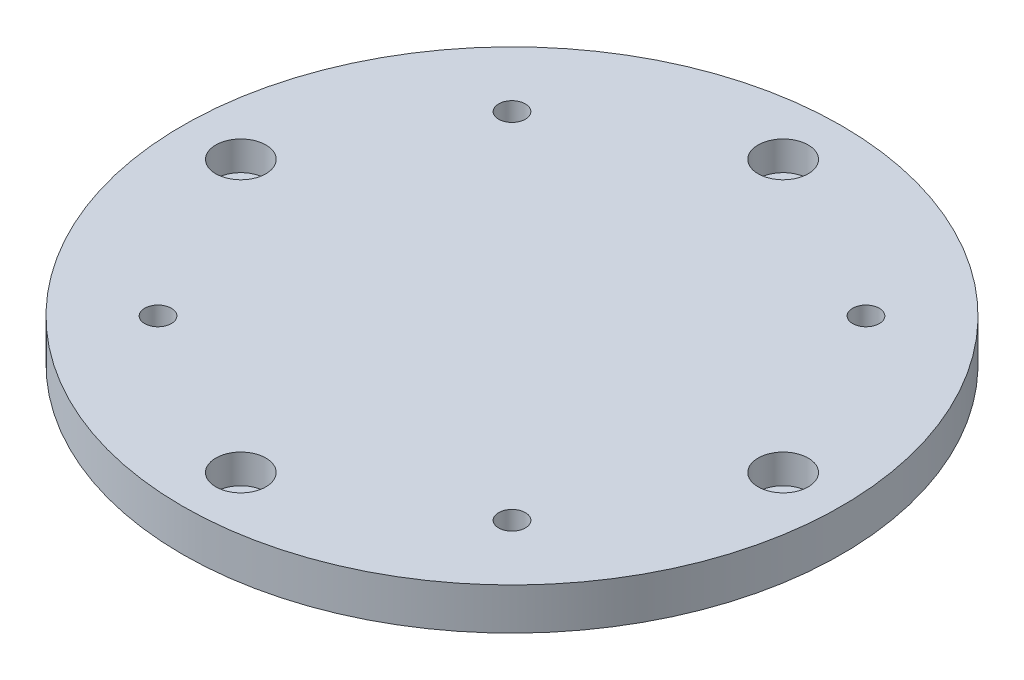
SolidWorks part; units mm, degrees
ref_plane "前视基准面" through (0, 0, 0) normal (0, 0, 1) x (1, 0, 0)
ref_plane "上视基准面" through (0, 0, 0) normal (0, 1, 0) x (1, 0, 0)
ref_plane "右视基准面" through (0, 0, 0) normal (1, 0, 0) x (0, 0, -1)
other "Configuration Table"
sketch "草图1" plane through (0, 0, 0) normal (0, 1, 0) x (1, 0, 0)
  circle A0 centre (0, 0) radius 39.5
  dimension "D1" = 79
extrude "凸台-拉伸1" add sketch "草图1" along normal blind 5
sketch "草图2" plane through (0, 5, 0) normal (0, 1, 0) x (1, 0, 0)
  line L0 (0, 37.2388) -> (0, -16.3257) construction
  line L1 (-34.8929, 0) -> (38.863, 0) construction
  circle A0 centre (0, 0) radius 32.5 construction
  circle A1 centre (0, 32.5) radius 1.5
  circle A2 centre (32.5, 0) radius 1.5
  circle A3 centre (0, -32.5) radius 1.5
  circle A4 centre (-32.5, 0) radius 1.5
  dimension "D1" = 65
  dimension "D2" = 3
  dimension "D3" = 3
  dimension "D4" = 3
  dimension "D5" = 3
extrude "切除-拉伸1" cut sketch "草图2" against normal through all both
sketch "草图3" plane through (0, 5, 0) normal (0, 1, 0) x (1, 0, 0)
  circle A0 centre (-32.5, 0) radius 3
  circle A1 centre (0, -32.5) radius 3
  circle A2 centre (32.5, 0) radius 3
  circle A3 centre (0, 32.5) radius 3
  dimension "D1" = 6
extrude "切除-拉伸2" cut sketch "草图3" against normal blind 3.5
sketch "草图5" plane through (0, 0, 0) normal (0, -1, 0) x (1, 0, 0)
  line L0 (0, 0) -> (21.2132, 21.2132) construction
  line L1 (0, 0) -> (30, 0) construction
  circle A0 centre (0, 0) radius 30 construction
  circle A5 centre (21.2132, 21.2132) radius 1.6
  circle A6 centre (21.2132, -21.2132) radius 1.6
  circle A7 centre (-21.2132, -21.2132) radius 1.6
  circle A8 centre (-21.2132, 21.2132) radius 1.6
  point P22 (0, 0)
  dimension "D1" = 60
  dimension "D4" = 3.2
  dimension "D3" = 45
  dimension "D5" = 4
extrude "切除-拉伸3" cut sketch "草图5" against normal through all
